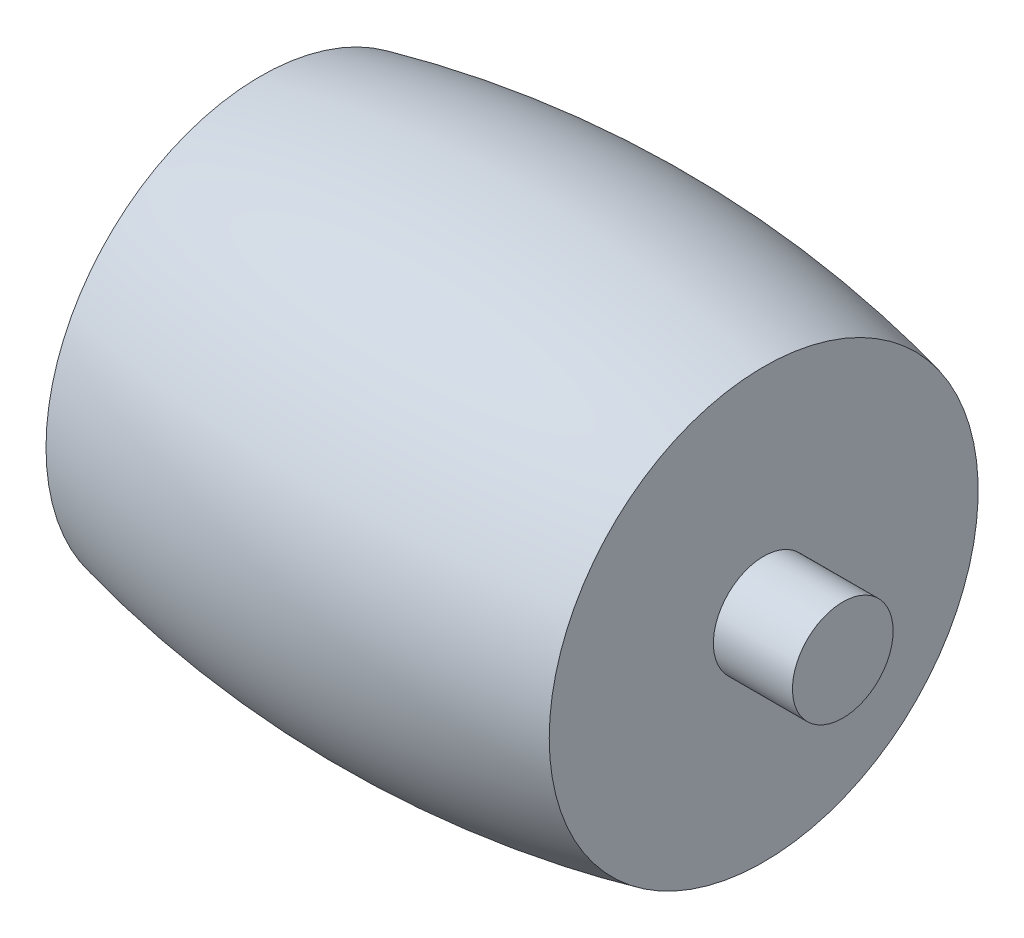
SolidWorks part; units mm, degrees
ref_plane "Front Plane" through (0, 0, 0) normal (0, 0, 1) x (1, 0, 0)
ref_plane "Top Plane" through (0, 0, 0) normal (0, 1, 0) x (1, 0, 0)
ref_plane "Right Plane" through (0, 0, 0) normal (1, 0, 0) x (0, 0, -1)
sketch "Sketch2" plane through (0, 0, 0) normal (0, 0, 1) x (1, 0, 0)
  line L0 (-18.415, 0) -> (18.415, 0) construction
  line L1 (0, 0) -> (0, 17.78) construction
  line L2 (-18.415, 0) -> (-18.415, 15.6976)
  line L3 (18.415, 0) -> (18.415, 15.6976)
  line L4 (0, 17.78) -> (0, -64.6836) construction
  line L6 (-18.415, 0) -> (18.415, 0)
  arc A0 (0, 17.78) -> (18.415, 15.6976) centre (0, -64.6836) cw
  arc A1 (0, 17.78) -> (-18.415, 15.6976) centre (0, -64.6836) ccw
  point P4 (0, 0)
  point P10 (0, 17.78)
  dimension "D1" = 36.83
  dimension "D2" = 17.78
  dimension "D3" = 82.4636
revolve "Revolve1" add sketch "Sketch2" angle 360 about L6
sketch "Sketch4" plane through (18.415, 0, 0) normal (1, 0, 0) x (0, 0, -1)
  circle A0 centre (0, 0) radius 3.683
  dimension "D1" = 7.366
extrude "Boss-Extrude1" add sketch "Sketch4" along normal blind 5.789
mirror "Mirror1" about plane through (0, 0, 0) normal (1, 0, 0) of "Boss-Extrude1"
